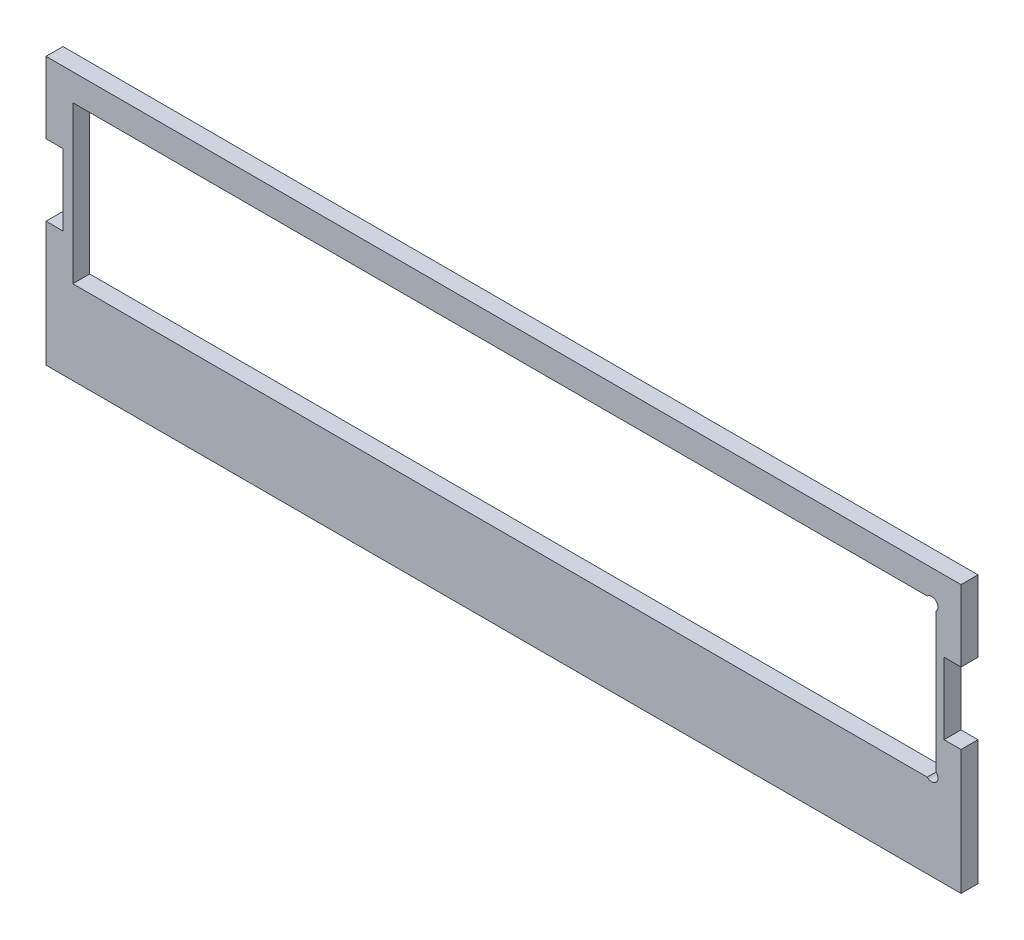
SolidWorks part; units mm, degrees
ref_plane "Front Plane" through (0, 0, 0) normal (0, 0, 1) x (1, 0, 0)
ref_plane "Top Plane" through (0, 0, 0) normal (0, 1, 0) x (1, 0, 0)
ref_plane "Right Plane" through (0, 0, 0) normal (1, 0, 0) x (0, 0, -1)
sketch "Sketch1" plane through (0, 0, 0) normal (0, 0, 1) x (1, 0, 0)
  line L4 (-1865.9199, 763.236) -> (-1865.9199, 503.736)
  line L5 (-1865.9199, 503.736) -> (-840.4586, 503.736)
  line L6 (-840.4586, 503.736) -> (-840.4586, 763.236)
  line L7 (-840.4586, 763.236) -> (-1865.9199, 763.236)
  line L8 (-1865.9199, 763.236) -> (-1865.9199, 463.5011)
  line L9 (-1865.9199, 463.5011) -> (-840.4586, 463.5011)
  line L10 (-840.4586, 463.5011) -> (-840.4586, 763.236)
  line L11 (-840.4586, 763.236) -> (-1865.9199, 763.236)
  dimension "D1" = 0
extrude "Boss-Extrude1" add sketch "Sketch1" along normal blind 19
sketch "Sketch2" plane through (0, 0, 19) normal (0, 0, 1) x (1, 0, 0)
  line L1 (-868.3199, 557.496) -> (-1835.9199, 557.496)
  line L2 (-868.3199, 557.496) -> (-868.3199, 733.236)
  line L3 (-868.3199, 733.236) -> (-1835.9199, 733.236)
  line L4 (-1835.9199, 557.496) -> (-1835.9199, 733.236)
extrude "Cut-Extrude1" cut sketch "Sketch2" against normal up to surface (19 mm away) up to face at (-1353.1892, 613.3685, 0)
sketch "Sketch3" plane through (0, 0, 19) normal (0, 0, 1) x (1, 0, 0)
  circle A2 centre (-873.3224, 728.3395) radius 7
  circle A3 centre (-873.3224, 562.3924) radius 7
  dimension "D1" = 14
extrude "Cut-Extrude2" cut sketch "Sketch3" against normal up to surface (19 mm away) up to face at (-1352.1199, 645.366, 0)
sketch "Sketch5" plane through (-840.4586, 0, 0) normal (1, 0, 0) x (0, 0, -1)
  line L0 (0, 463.5011) -> (0, 763.236) construction
  line L1 (0, 683.236) -> (-19, 683.236)
  line L2 (0, 683.236) -> (0, 603.236)
  line L3 (0, 603.236) -> (-19, 603.236)
  line L4 (-19, 683.236) -> (-19, 603.236)
  line L5 (-19, 463.5011) -> (-19, 763.236) construction
  line L6 (-19, 763.236) -> (0, 763.236) construction
  dimension "D1" = 80
extrude "Cut-Extrude3" cut sketch "Sketch5" against normal blind 19
sketch "Sketch6" plane through (-1865.9199, 0, 0) normal (-1, 0, 0) x (0, 0, 1)
  line L0 (0, 763.236) -> (0, 463.5011) construction
  line L1 (0, 603.236) -> (19, 603.236)
  line L2 (0, 603.236) -> (0, 683.236)
  line L3 (0, 683.236) -> (19, 683.236)
  line L4 (19, 603.236) -> (19, 683.236)
  line L5 (19, 763.236) -> (19, 463.5011) construction
extrude "Cut-Extrude4" cut sketch "Sketch6" against normal blind 19
hole_wizard "M5 Clearance Hole1" positions "Sketch7" profile "Sketch8"
sketch "Sketch7" plane through (-1324.1983, -78.4878, -19) normal (0, 0, -1) x (1, 0, 0)
  point P0 (-477.7447, -772.7192)
  point P3 (-477.7447, -723.8537)
  point P6 (-477.7447, -674.9837)
  point P9 (416.877, -772.7192)
  point P12 (416.877, -723.8487)
  point P15 (416.877, -674.9892)
  point P18 (100.2351, -718.9325)
  point P20 (-182.4777, -714.0157)
sketch "Sketch8" plane through (-1801.943, 694.2314, -19) normal (1, 0, 0) x (0, 1, 0)
  line L0 (0, 0) -> (0, 34)
  line L1 (0, 34) -> (2.75, 32.3476)
  line L2 (2.75, 32.3476) -> (2.75, 0)
  line L3 (2.75, 0) -> (0, 0)
  line L4 (0, 34) -> (-2.75, 32.3476) construction
  line L5 (0, -6.35) -> (0, 107.95) construction
  dimension "Hole Dia." = 5.5
  dimension "Hole Depth" = 34
  dimension "Drill Angle" = 118
